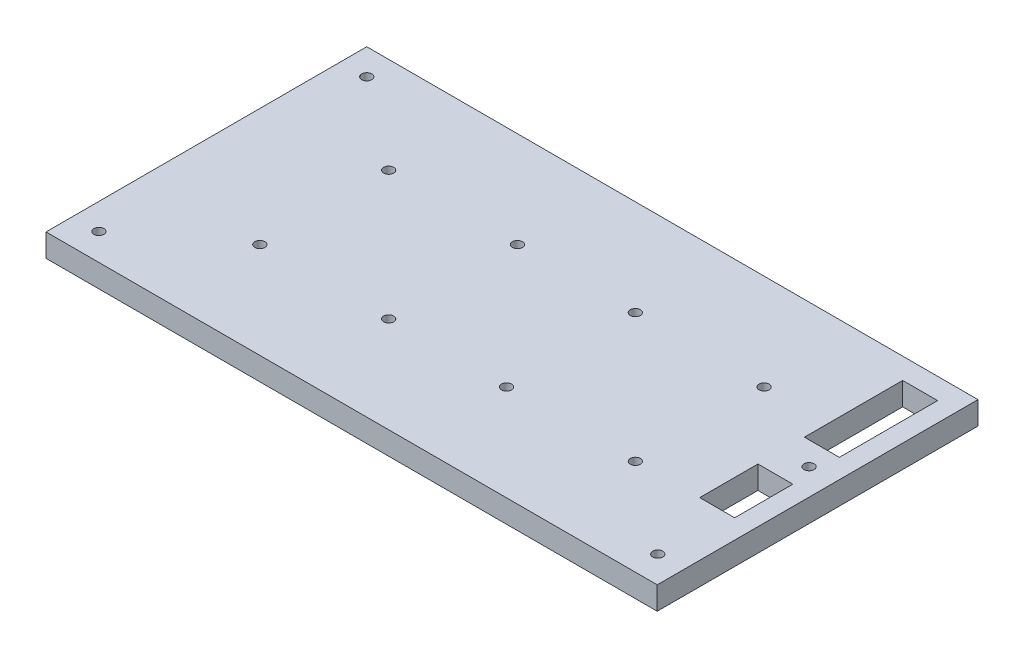
SolidWorks part; units mm, degrees
ref_plane "Front Plane" through (0, 0, 0) normal (0, 0, 1) x (1, 0, 0)
ref_plane "Top Plane" through (0, 0, 0) normal (0, 1, 0) x (1, 0, 0)
ref_plane "Right Plane" through (0, 0, 0) normal (1, 0, 0) x (0, 0, -1)
sketch "Sketch1" plane through (0, 0, 0) normal (0, 1, 0) x (1, 0, 0)
  line L0 (0, 0) -> (0, 69.98)
  line L1 (0, 69.98) -> (-133.35, 69.98)
  line L2 (-133.35, 69.98) -> (-133.35, 0)
  line L3 (-133.35, 0) -> (0, 0)
  dimension "D1" = 133.35
  dimension "D2" = 69.98
extrude "platform_thickness" add sketch "Sketch1" along normal blind 5
sketch "Sketch2" plane through (0, 5, 0) normal (0, 1, 0) x (1, 0, 0)
  line L0 (-133.35, 69.98) -> (-133.35, 0) construction
  line L1 (0, 69.98) -> (-133.35, 69.98) construction
  line L2 (-133.35, 0) -> (0, 0) construction
  line L4 (0, 0) -> (0, 69.98) construction
  circle A4 centre (-5.75, 38.88) radius 1.1
  circle A5 centre (-5.75, 5.86) radius 1.1
  circle A6 centre (-127.67, 5.86) radius 1.1
  circle A7 centre (-127.67, 64.29) radius 1.1
  point P12 (-127.3403, 69.8037)
  dimension "D1" = 2.2
  dimension "D2" = 5.68
  dimension "D3" = 5.69
  dimension "D4" = 5.68
  dimension "D5" = 5.86
  dimension "D6" = 5.86
  dimension "D7" = 5.75
  dimension "D8" = 5.75
  dimension "D9" = 33.02
extrude "mounting_holes_1" cut sketch "Sketch2" against normal through all
sketch "Sketch4" plane through (0, 5, 0) normal (0, 1, 0) x (1, 0, 0)
  line L0 (-25.7167, 49.04) -> (-25.7167, 20.94) construction
  line L1 (-25.7167, 20.94) -> (-53.8167, 20.94) construction
  line L2 (-25.7167, 49.04) -> (-53.8167, 49.04) construction
  line L3 (-53.8167, 49.04) -> (-53.8167, 20.94) construction
  line L4 (-79.5333, 49.04) -> (-79.5333, 20.94) construction
  line L5 (-79.5333, 20.94) -> (-107.6333, 20.94) construction
  line L6 (-107.6333, 20.94) -> (-107.6333, 49.04) construction
  line L7 (-107.6333, 49.04) -> (-79.5333, 49.04) construction
  line L8 (-53.8167, 49.04) -> (-53.8167, 69.98) construction
  line L9 (0, 69.98) -> (-133.35, 69.98) construction
  line L10 (-53.8167, 20.94) -> (-53.8167, 0) construction
  line L11 (-133.35, 0) -> (0, 0) construction
  line L12 (-107.6333, 20.94) -> (-107.6333, 0) construction
  line L13 (-107.6333, 49.04) -> (-107.6333, 69.98) construction
  line L14 (-107.6333, 49.04) -> (-133.35, 49.04) construction
  line L15 (-133.35, 69.98) -> (-133.35, 0) construction
  line L16 (-53.8167, 49.04) -> (-79.5333, 49.04) construction
  line L17 (-25.7167, 49.04) -> (0, 49.04) construction
  line L18 (0, 0) -> (0, 69.98) construction
  circle A0 centre (-25.7167, 49.04) radius 1.1
  circle A1 centre (-25.7167, 20.94) radius 1.1
  circle A2 centre (-53.8167, 49.04) radius 1.1
  circle A3 centre (-53.8167, 20.94) radius 1.1
  circle A4 centre (-79.5333, 49.04) radius 1.1
  circle A5 centre (-79.5333, 20.94) radius 1.1
  circle A6 centre (-107.6333, 49.04) radius 1.1
  circle A7 centre (-107.6333, 20.94) radius 1.1
  dimension "D1" = 2.2
  dimension "D2" = 28.1
  dimension "D3" = 28.1
  dimension "D4" = 28.1
  dimension "D5" = 28.1
extrude "mounting_holes_2" cut sketch "Sketch4" against normal through all
sketch "Sketch3" plane through (0, 5, 0) normal (0, 1, 0) x (1, 0, 0)
  line L4 (-4.22, 21.11) -> (-4.22, 33.81)
  line L6 (-4.22, 33.81) -> (-11.84, 33.81)
  line L8 (-11.84, 33.81) -> (-11.84, 21.11)
  line L10 (-11.84, 21.11) -> (-4.22, 21.11)
  line L11 (-4.22, 43.95) -> (-11.84, 43.95)
  line L12 (-11.84, 43.95) -> (-11.84, 65.39)
  line L13 (-11.84, 65.39) -> (-4.22, 65.39)
  line L14 (-4.22, 65.39) -> (-4.22, 43.95)
  line L15 (0, 0) -> (0, 69.98) construction
  line L16 (-133.35, 0) -> (0, 0) construction
  line L17 (0, 69.98) -> (-133.35, 69.98) construction
  circle A1 centre (-5.75, 38.88) radius 1.1 construction
  dimension "D5" = 5.07
  dimension "D1" = 7.62
  dimension "D2" = 4.22
  dimension "D3" = 21.11
  dimension "D4" = 12.7
  dimension "D6" = 4.59
extrude "cable_management_hole" cut sketch "Sketch3" against normal through all
